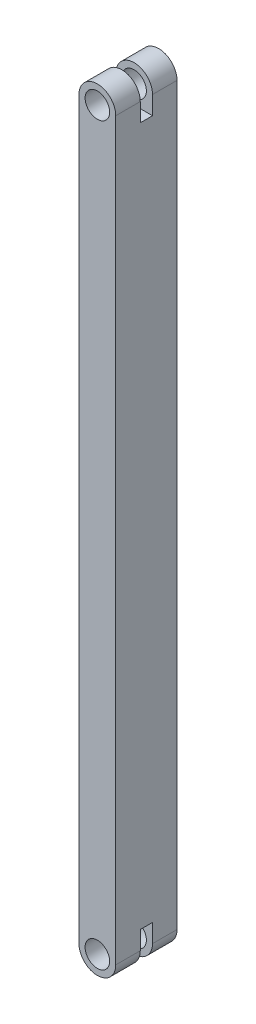
SolidWorks part; units mm, degrees
ref_plane "前视基准面" through (0, 0, 0) normal (0, 0, 1) x (1, 0, 0)
ref_plane "上视基准面" through (0, 0, 0) normal (0, 1, 0) x (1, 0, 0)
ref_plane "右视基准面" through (0, 0, 0) normal (1, 0, 0) x (0, 0, -1)
other "Configuration Table"
sketch "草图1" plane through (0, 0, 0) normal (0, 0, 1) x (1, 0, 0)
  line L0 (0, 0) -> (0, 300) construction
  line L1 (-7.5, 0) -> (-7.5, 300)
  line L2 (7.5, 0) -> (7.5, 300)
  arc A0 (-7.5, 0) -> (7.5, 0) centre (0, 0) ccw
  arc A1 (7.5, 300) -> (-7.5, 300) centre (0, 300) ccw
  point P3 (0, 150)
  dimension "D1" = 7.5
  dimension "D2" = 300
extrude "凸台-拉伸1" add sketch "草图1" along normal blind 25
sketch "草图2" plane through (7.5, 0, 0) normal (1, 0, 0) x (0, 0, -1)
  line L0 (0, 307.5) -> (-25, 307.5) construction
  line L1 (-15, 307.5) -> (-10, 307.5)
  line L2 (-15, 307.5) -> (-15, 292.5)
  line L3 (-15, 292.5) -> (-10, 292.5)
  line L4 (-10, 307.5) -> (-10, 292.5)
  line L5 (-25, -7.5) -> (0, -7.5) construction
  line L6 (-15, -7.5) -> (-10, -7.5)
  line L7 (-15, -7.5) -> (-15, 7.5)
  line L8 (-15, 7.5) -> (-10, 7.5)
  line L9 (-10, -7.5) -> (-10, 7.5)
  line L10 (0, 0) -> (0, 300) construction
  point P10 (-16.8444, -7.5)
  point P13 (-8.1556, -7.5)
  dimension "D1" = 5
  dimension "D2" = 5
  dimension "D3" = 15
  dimension "D4" = 15
  dimension "D5" = 10
extrude "切除-拉伸1" cut sketch "草图2" against normal through all
sketch "草图3" plane through (0, 0, 25) normal (0, 0, 1) x (1, 0, 0)
  circle A0 centre (0, 300) radius 5
  circle A1 centre (0, 0) radius 5
  dimension "D1" = 10
extrude "切除-拉伸2" cut sketch "草图3" against normal through all
